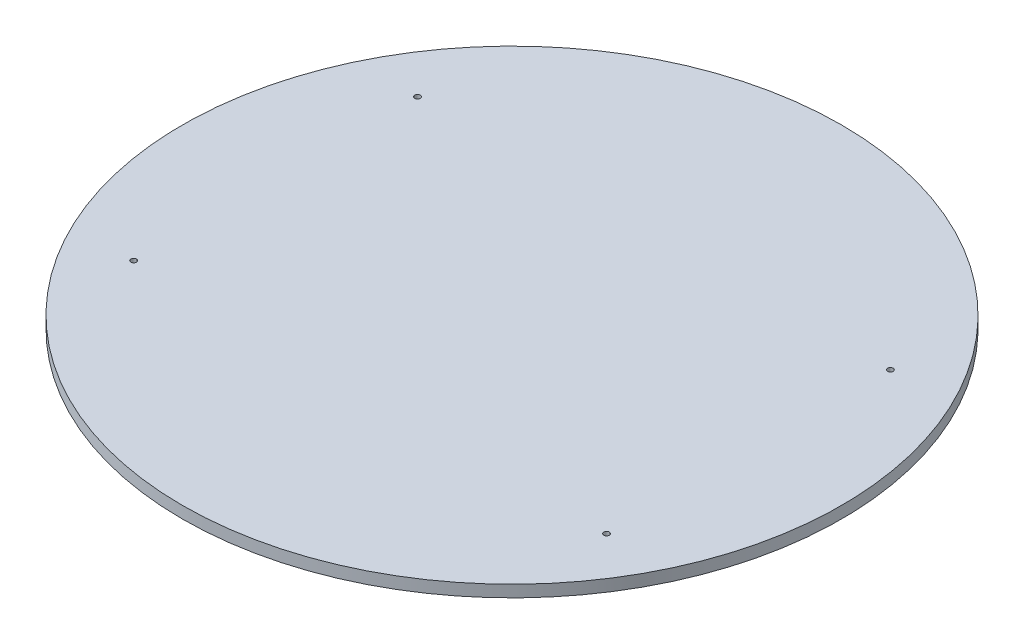
SolidWorks part; units mm, degrees
ref_plane "Front Plane" through (0, 0, 0) normal (0, 0, 1) x (1, 0, 0)
ref_plane "Top Plane" through (0, 0, 0) normal (0, 1, 0) x (1, 0, 0)
ref_plane "Right Plane" through (0, 0, 0) normal (1, 0, 0) x (0, 0, -1)
sketch "Sketch1" plane through (0, 0, 0) normal (0, 1, 0) x (1, 0, 0)
  circle A0 centre (0, 0) radius 177
  circle A1 centre (-127, -76.2) radius 1.5
  circle A2 centre (-127, 76.2) radius 1.5
  circle A3 centre (127, 76.2) radius 1.5
  circle A4 centre (127, -76.2) radius 1.5
  dimension "D1" = 354
  dimension "D2" = 3
  dimension "D3" = 3
  dimension "D4" = 3
  dimension "D5" = 3
  dimension "D8" = 254
  dimension "D6" = 152.4
  dimension "D7" = 152.4
  dimension "D9" = 254
  dimension "D10" = 0
  dimension "D11" = 127
  dimension "D12" = 76.2
extrude "Boss-Extrude1" add sketch "Sketch1" along normal blind 6.35
